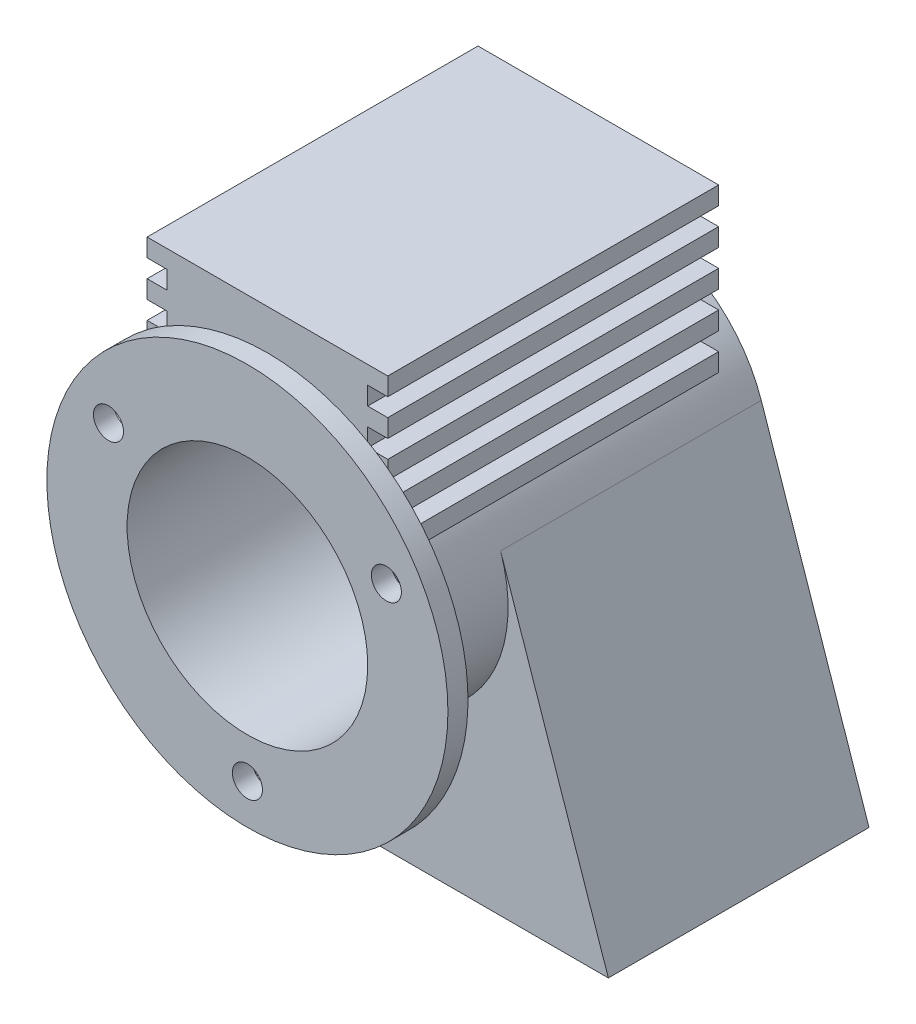
SolidWorks part; units mm, degrees
material "Gray Cast Iron"
ref_plane "Front Plane" through (0, 0, 0) normal (0, 0, 1) x (1, 0, 0)
ref_plane "Top Plane" through (0, 0, 0) normal (0, 1, 0) x (1, 0, 0)
ref_plane "Right Plane" through (0, 0, 0) normal (1, 0, 0) x (0, 0, -1)
sketch "Sketch1" plane through (0, 0, 0) normal (0, 0, 1) x (1, 0, 0)
  line L0 (3, 0) -> (-3, 0)
  line L1 (-3, 0) -> (-3, -0.45)
  line L2 (-3, -0.45) -> (-2.5, -0.45)
  line L3 (-2.5, -0.45) -> (-2.5, -0.9)
  line L4 (-2.5, -0.9) -> (-3, -0.9)
  line L5 (-3, -0.9) -> (-3, -1.35)
  line L6 (-3, -1.35) -> (-2.5, -1.35)
  line L7 (-2.5, -1.35) -> (-2.5, -1.8)
  line L8 (-2.5, -1.8) -> (-3, -1.8)
  line L9 (-3, -1.8) -> (-3, -2.25)
  line L10 (-3, -2.25) -> (-2.5, -2.25)
  line L11 (-2.5, -2.25) -> (-2.5, -2.7)
  line L12 (-2.5, -2.7) -> (-3, -2.7)
  line L13 (-3, -2.7) -> (-3, -3.15)
  line L14 (-3, -3.15) -> (-2.5, -3.15)
  line L15 (-3, -5.4) -> (-3, -5.85)
  line L16 (-2.5, -3.15) -> (-2.5, -3.6)
  line L17 (-2.5, -3.6) -> (-3, -3.6)
  line L18 (-3, -3.6) -> (-3, -4.05)
  line L19 (-3, -4.05) -> (-2.5, -4.05)
  line L20 (-2.5, -4.05) -> (-2.5, -4.5)
  line L21 (-2.5, -4.5) -> (-3, -4.5)
  line L22 (-3, -4.5) -> (-3, -4.95)
  line L23 (-3, -4.95) -> (-2.5, -4.95)
  line L24 (-2.5, -4.95) -> (-2.5, -5.4)
  line L25 (-2.5, -5.4) -> (-3, -5.4)
  line L26 (-3, -5.85) -> (-2.5, -5.85)
  line L27 (-2.5, -5.85) -> (-2.5, -6.3)
  line L29 (0, 0) -> (0, -7.1358) construction
  line L31 (2.5, -5.85) -> (2.5, -6.3)
  line L32 (3, -5.85) -> (2.5, -5.85)
  line L33 (2.5, -5.4) -> (3, -5.4)
  line L34 (2.5, -4.95) -> (2.5, -5.4)
  line L35 (3, -4.95) -> (2.5, -4.95)
  line L36 (3, -4.5) -> (3, -4.95)
  line L37 (2.5, -4.5) -> (3, -4.5)
  line L38 (2.5, -4.05) -> (2.5, -4.5)
  line L39 (3, -4.05) -> (2.5, -4.05)
  line L40 (3, -3.6) -> (3, -4.05)
  line L41 (2.5, -3.6) -> (3, -3.6)
  line L42 (2.5, -3.15) -> (2.5, -3.6)
  line L43 (3, -5.4) -> (3, -5.85)
  line L44 (3, -3.15) -> (2.5, -3.15)
  line L45 (3, -2.7) -> (3, -3.15)
  line L46 (2.5, -2.7) -> (3, -2.7)
  line L47 (2.5, -2.25) -> (2.5, -2.7)
  line L48 (3, -2.25) -> (2.5, -2.25)
  line L49 (3, -1.8) -> (3, -2.25)
  line L50 (2.5, -1.8) -> (3, -1.8)
  line L51 (2.5, -1.35) -> (2.5, -1.8)
  line L52 (3, -1.35) -> (2.5, -1.35)
  line L53 (3, -0.9) -> (3, -1.35)
  line L54 (2.5, -0.9) -> (3, -0.9)
  line L55 (2.5, -0.45) -> (2.5, -0.9)
  line L56 (3, -0.45) -> (2.5, -0.45)
  line L57 (3, 0) -> (3, -0.45)
  line L58 (-2.5, -6.3) -> (2.5, -6.3)
  point P4 (0, 0)
  dimension "D1" = 6
  dimension "D3" = 0.5
  dimension "D4" = 0.5
  dimension "D5" = 0.5
  dimension "D6" = 0.5
  dimension "D7" = 0.5
  dimension "D8" = 0.5
  dimension "D9" = 0.5
  dimension "D10" = 0.45
  dimension "D11" = 0.45
  dimension "D12" = 0.45
  dimension "D13" = 0.9
  dimension "D14" = 0.9
  dimension "D15" = 0.9
  dimension "D16" = 0.9
  dimension "D17" = 0.45
  dimension "D18" = 0.5
  dimension "D19" = 0.5
  dimension "D20" = 0.5
  dimension "D21" = 0.5
  dimension "D22" = 0.5
  dimension "D23" = 0.9
  dimension "D24" = 0.9
  dimension "D25" = 0.5
  dimension "D26" = 0.45
  dimension "D27" = 0.45
  dimension "D28" = 6.3
  dimension "D30" = 0.45
extrude "Boss-Extrude1" add sketch "Sketch1" along normal mid plane 8.25
sketch "Sketch2" plane through (0, 0, 4.125) normal (0, 0, 1) x (1, 0, 0)
  line L0 (3, 0) -> (-3, 0) construction
  circle A0 centre (0, -6) radius 5
  dimension "D1" = 10
  dimension "D2" = 6
extrude "Boss-Extrude2" add sketch "Sketch2" along normal blind 0.5
sketch "Sketch3" plane through (0, 0, 4.625) normal (0, 0, 1) x (1, 0, 0)
  circle A0 centre (0, -6) radius 3.5
  dimension "D1" = 7
extrude "Cut-Extrude1" cut sketch "Sketch3" against normal blind 9
sketch "Sketch4" plane through (0, 0, 4.625) normal (0, 0, 1) x (1, 0, 0)
  line L0 (0, -6) -> (6.7858, -6) construction
  line L1 (0, -6) -> (5.5598, -2.79) construction
  circle A0 centre (0, -6) radius 4 construction
  circle A1 centre (3.4641, -4) radius 0.375
  dimension "D1" = 8
  dimension "D3" = 0.75
  dimension "D2" = 30
extrude "Cut-Extrude2" cut sketch "Sketch4" against normal up to surface (0.5 mm away) up to face at (0, -3.6896, 4.125)
pattern_circular "CirPattern1" count 3 over 360 about axis through (0, -6, 0) along (0, 0, 1) of "Cut-Extrude2"
ref_plane "Plane1" through (0, 0, -4.875) normal (0, 0, 1) x (1, 0, 0)
sketch "Sketch5" plane through (0, 0, -4.875) normal (0, 0, 1) x (1, 0, 0)
  line L0 (6, -12.75) -> (-6, -12.75)
  line L1 (6, -12.75) -> (3.3126, -4.8702)
  line L2 (-6, -12.75) -> (-3.3126, -4.8702)
  arc A0 (3.3126, -4.8702) -> (-3.3126, -4.8702) centre (0, -6) ccw
  point P6 (0, -12.75)
  dimension "D1" = 7
  dimension "D2" = 12
  dimension "D3" = 6.75
extrude "Boss-Extrude3" add sketch "Sketch5" along normal blind 6.5
sketch "Sketch6" plane through (0, 0, -4.875) normal (0, 0, -1) x (-1, 0, 0)
  circle A0 centre (0, -6) radius 0.75
  dimension "D1" = 1.5
sketch "Sketch7" plane through (0, 0, 4.625) normal (0, 0, 1) x (1, 0, 0)
  circle A0 centre (0, -6) radius 3.5
  dimension "D1" = 7
extrude "Boss-Extrude4" add sketch "Sketch7" against normal blind 6.5
sketch "Sketch8" plane through (0, 0, 4.625) normal (0, 0, 1) x (1, 0, 0)
  circle A0 centre (0, -6) radius 3
  dimension "D1" = 6
extrude "Cut-Extrude3" cut sketch "Sketch8" against normal blind 9
extrude "Cut-Extrude4" cut sketch "Sketch6" against normal blind 9 contours A0
